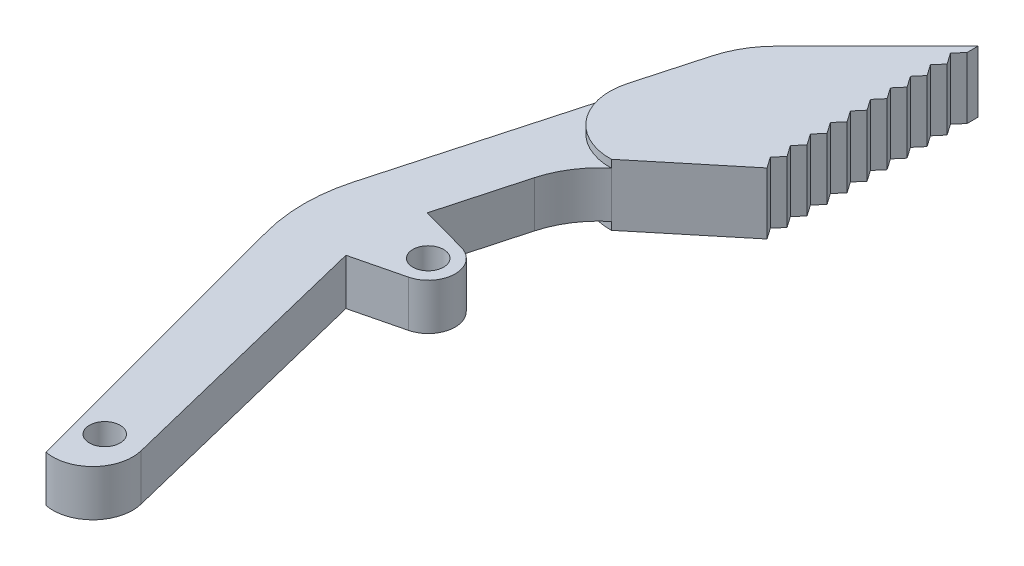
SolidWorks part; units mm, degrees
ref_plane "Front Plane" through (0, 0, 0) normal (0, 0, 1) x (1, 0, 0)
ref_plane "Top Plane" through (0, 0, 0) normal (0, 1, 0) x (1, 0, 0)
ref_plane "Right Plane" through (0, 0, 0) normal (1, 0, 0) x (0, 0, -1)
sketch "Sketch1" plane through (0, 0, 0) normal (0, 1, 0) x (1, 0, 0)
  line L0 (93, 352.5) -> (479.4671, 352.5) construction
  line L1 (156.7243, 188.7494) -> (104.3625, 384.6757)
  line L2 (104.6195, 440.839) -> (155.1087, 623.0565)
  line L3 (170.5037, 649.4616) -> (236.0394, 714.9973)
  line L4 (236.0394, 714.9973) -> (236.0394, 577.9338)
  line L5 (236.0394, 577.9338) -> (180.6004, 532.2534)
  line L6 (160.8955, 501.8307) -> (142.174, 433.6307)
  line L7 (141.7737, 403.4022) -> (186.8449, 220.3581)
  arc A0 (104.3625, 384.6757) -> (104.6195, 440.839) centre (207.6713, 412.2852) cw
  arc A1 (186.8449, 220.3581) -> (156.7243, 188.7494) centre (161.6975, 214.166) cw
  arc A2 (155.1087, 623.0565) -> (170.5037, 649.4616) centre (212.9301, 607.0352) cw
  arc A3 (142.174, 433.6307) -> (141.7737, 403.4022) centre (200.0335, 417.7476) ccw
  arc A4 (180.6004, 532.2534) -> (160.8955, 501.8307) centre (218.7551, 485.9477) ccw
  dimension "D1" = 60
  dimension "D2" = 60
  dimension "D3" = 60
extrude "Boss-Extrude1" add sketch "Sketch1" along normal blind 50
sketch "Sketch2" plane through (0, 50, 0) normal (0, 1, 0) x (1, 0, 0)
  circle A0 centre (120.4927, 416.6946) radius 10
  dimension "D1" = 20
extrude "Cut-Extrude1" cut sketch "Sketch2" against normal blind 145
sketch "Sketch3" plane through (0, 50, 0) normal (0, 1, 0) x (1, 0, 0)
  circle A0 centre (165.6527, 217.9977) radius 10
  dimension "D1" = 20
extrude "Cut-Extrude2" cut sketch "Sketch3" against normal blind 145
scale "Scale1" scale about centroid uniform scaling yes scale factor 0.2
sketch "Sketch4" plane through (0, 30, 0) normal (0, 1, 0) x (1, 0, 0)
  line L0 (167.3334, 464.6058) -> (160.8073, 462.9989)
  line L1 (169.5057, 427.6728) -> (160.4915, 464.2816) construction
  line L2 (167.4231, 471.3794) -> (161.3202, 473.0547)
  line L3 (160.5715, 470.3273) -> (164.3159, 483.9673) construction
  line L4 (160.5715, 470.3273) -> (161.3202, 473.0547)
  line L5 (160.8073, 462.9989) -> (160.4915, 464.2816)
  arc A0 (167.3334, 464.6058) -> (167.4231, 471.3794) centre (166.4966, 468.0043) ccw
  arc A1 (160.5715, 470.3273) -> (160.4915, 464.2816) centre (172.1435, 467.1507) ccw construction
  arc A2 (160.5715, 470.3273) -> (160.4915, 464.2816) centre (172.1435, 467.1507) ccw
  circle A3 centre (166.4966, 468.0043) radius 2
  dimension "D1" = 7
  dimension "D2" = 4
extrude "Boss-Extrude2" add sketch "Sketch4" against normal blind 10
sketch "Sketch5" plane through (0, 20, 0) normal (0, -1, 0) x (1, 0, 0)
  line L9 (167.3334, -464.6058) -> (160.8073, -462.9989)
  line L10 (160.8073, -462.9989) -> (169.5057, -427.6728)
  line L11 (163.4816, -421.3511) -> (153.0093, -460.5363)
  line L12 (153.0607, -471.769) -> (163.1585, -508.2125)
  line L13 (166.2375, -513.4935) -> (179.3446, -526.6007)
  line L14 (179.3446, -526.6007) -> (179.3446, -499.1879)
  line L15 (179.3446, -499.1879) -> (168.2568, -490.0519)
  line L16 (164.3159, -483.9673) -> (161.3202, -473.0547)
  line L17 (161.3202, -473.0547) -> (167.4231, -471.3794)
  line L18 (167.3334, -464.6058) -> (160.8073, -462.9989)
  line L19 (160.8073, -462.9989) -> (169.5057, -427.6728)
  line L20 (163.4816, -421.3511) -> (153.0093, -460.5363)
  line L21 (153.0607, -471.769) -> (163.1585, -508.2125)
  line L22 (166.2375, -513.4935) -> (179.3446, -526.6007)
  line L23 (179.3446, -526.6007) -> (179.3446, -499.1879)
  line L24 (179.3446, -499.1879) -> (168.2568, -490.0519)
  line L25 (164.3159, -483.9673) -> (161.3202, -473.0547)
  line L26 (161.3202, -473.0547) -> (167.4231, -471.3794)
  arc A5 (169.5057, -427.6728) -> (163.4816, -421.3511) centre (164.4762, -426.4344) ccw
  arc A6 (153.0093, -460.5363) -> (153.0607, -471.769) centre (173.671, -466.0582) ccw
  arc A7 (163.1585, -508.2125) -> (166.2375, -513.4935) centre (174.7228, -505.0082) ccw
  arc A8 (164.3159, -483.9673) -> (168.2568, -490.0519) centre (175.8878, -480.7907) ccw
  arc A9 (167.4231, -471.3794) -> (167.3334, -464.6058) centre (166.4966, -468.0043) ccw
  arc A10 (169.5057, -427.6728) -> (163.4816, -421.3511) centre (164.4762, -426.4344) ccw
  arc A11 (153.0093, -460.5363) -> (153.0607, -471.769) centre (173.671, -466.0582) ccw
  arc A12 (163.1585, -508.2125) -> (166.2375, -513.4935) centre (174.7228, -505.0082) ccw
  arc A13 (164.3159, -483.9673) -> (168.2568, -490.0519) centre (175.8878, -480.7907) ccw
  arc A14 (167.4231, -471.3794) -> (167.3334, -464.6058) centre (166.4966, -468.0043) ccw
  dimension "D1" = 0
extrude "Cut-Extrude3" cut sketch "Sketch5" against normal blind 4
sketch "Sketch6" plane through (0, 30, 0) normal (0, 1, 0) x (1, 0, 0)
  circle A0 centre (156.2353, 466.9401) radius 2 construction
  circle A1 centre (156.2353, 466.9401) radius 2
extrude "Boss-Extrude3" add sketch "Sketch6" against normal blind 6
sketch "Sketch7" plane through (0, 30, 0) normal (0, 1, 0) x (1, 0, 0)
  line L0 (179.3446, 526.6007) -> (166.2375, 513.4935) construction
  line L1 (179.3446, 526.6007) -> (166.2375, 513.4935)
  line L2 (163.1585, 508.2125) -> (153.0607, 471.769) construction
  line L3 (163.1585, 508.2125) -> (160.777, 499.6174)
  line L4 (168.2568, 490.0519) -> (179.3446, 499.1879) construction
  line L5 (168.2568, 490.0519) -> (179.3446, 499.1879)
  line L6 (179.3446, 499.1879) -> (179.3446, 526.6007) construction
  line L7 (179.3446, 499.1879) -> (179.3446, 526.6007)
  arc A0 (166.2375, 513.4935) -> (163.1585, 508.2125) centre (174.7228, 505.0082) ccw construction
  arc A1 (166.2375, 513.4935) -> (163.1585, 508.2125) centre (174.7228, 505.0082) ccw
  arc A2 (168.2568, 490.0519) -> (160.777, 499.6174) centre (168.0545, 497.6009) cw
extrude "Boss-Extrude4" add sketch "Sketch7" along normal blind 1
ref_plane "Plane1" through (0, 27, 0) normal (0, 1, 0) x (1, 0, 0)
mirror "Mirror2" about plane through (0, 27, 0) normal (0, 1, 0) of "Boss-Extrude4"
sketch "Sketch8" plane through (0, 31, 0) normal (0, 1, 0) x (1, 0, 0)
  line L0 (179.3446, 499.1879) -> (178.3446, 500.6147)
  line L3 (178.3446, 500.6147) -> (179.3446, 501.7879)
  line L4 (179.3446, 499.1879) -> (179.3446, 526.6007) construction
  line L5 (179.3446, 501.7879) -> (178.3446, 503.2147)
  line L6 (178.3446, 503.2147) -> (179.3446, 504.3879)
  line L7 (179.3446, 504.3879) -> (179.3446, 499.1879)
  line M9 (179.3446, 499.1879) -> (179.3446, 526.6007)
  dimension "D1" = 1
  dimension "D2" = 2.6
extrude "Cut-Extrude4" cut sketch "Sketch8" against normal blind 10 contours L3 L0 M9 | L6 L5 M9
pattern_linear "LPattern1" count 5 spacing 5.2 along (0, 0, -1) of "Cut-Extrude4"
